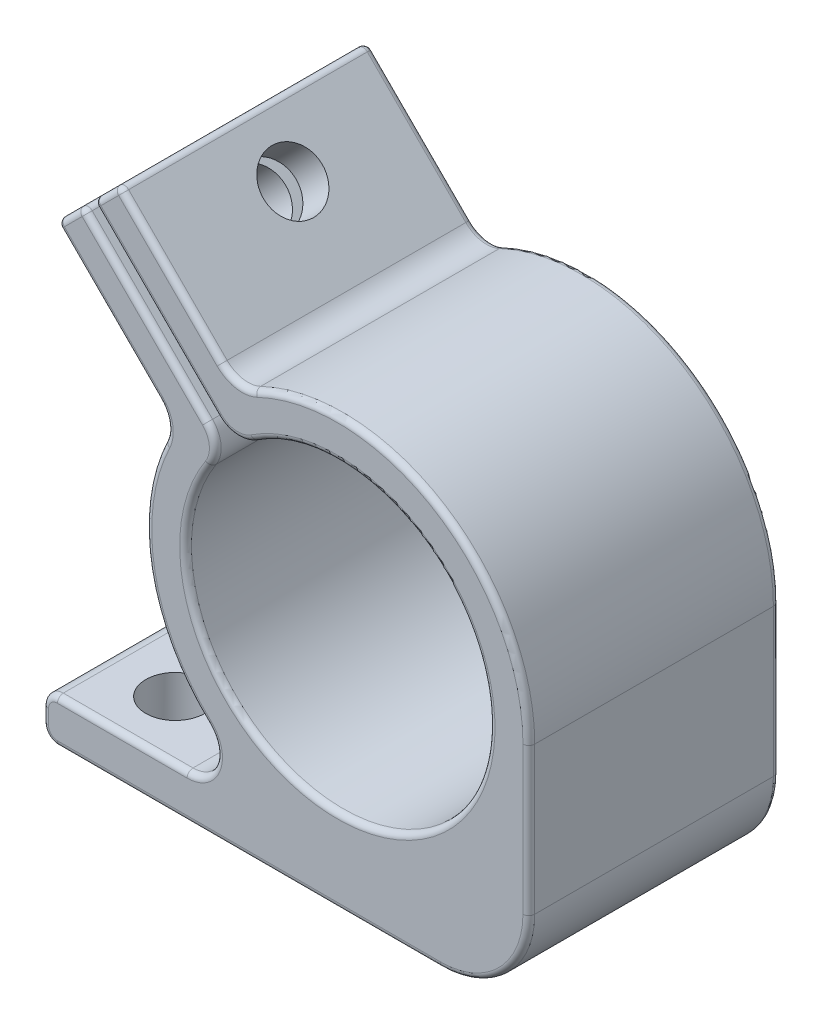
SolidWorks part; units mm, degrees
ref_plane "前视基准面" through (0, 0, 0) normal (0, 0, 1) x (1, 0, 0)
ref_plane "上视基准面" through (0, 0, 0) normal (0, 1, 0) x (1, 0, 0)
ref_plane "右视基准面" through (0, 0, 0) normal (1, 0, 0) x (0, 0, -1)
sketch "草图1" plane through (0, 0, 0) normal (0, 0, 1) x (1, 0, 0)
  line L0 (-9.5, -6.5) -> (-5.099, -6.5)
  line L1 (-9.5, -8) -> (3.5, -8)
  line L2 (-10, -7) -> (-10, -7.5)
  line L5 (0, 0) -> (-8.4853, 8.4853) construction
  line L6 (-7.2832, 9.4045) -> (-3.9393, 6.0607)
  line L7 (-8.8035, 8.1671) -> (-9.4045, 7.566)
  line L8 (0, 0) -> (0, -2.1091) construction
  line L9 (-8.1671, 8.5206) -> (-4.0812, 4.4347)
  line L10 (-8.1671, 8.8035) -> (-7.566, 9.4045)
  line L11 (-9.4045, 7.2832) -> (-6.0607, 3.9393)
  line L12 (6.5, 0) -> (6.5, -5)
  line L13 (-8.5206, 8.1671) -> (-4.4347, 4.0812)
  line L14 (0, 0) -> (0, -15.0845) construction
  arc A0 (-4.3057, 2.8254) -> (-2.8254, 4.3057) centre (0, 0) ccw
  arc A1 (-5.8654, 2.8013) -> (-4.4192, -4.7667) centre (0, 0) ccw
  arc A2 (6.5, -5) -> (3.5, -8) centre (3.5, -5) cw
  arc A3 (-4.4192, -4.7667) -> (-5.099, -6.5) centre (-5.099, -5.5) cw
  arc A6 (-9.5, -8) -> (-10, -7.5) centre (-9.5, -7.5) cw
  arc A7 (-10, -7) -> (-9.5, -6.5) centre (-9.5, -7) cw
  arc A8 (6.5, 0) -> (-2.8013, 5.8654) centre (0, 0) ccw
  arc A9 (-8.1671, 8.8035) -> (-8.1671, 8.5206) centre (-8.0257, 8.6621) ccw
  arc A10 (-7.2832, 9.4045) -> (-7.566, 9.4045) centre (-7.4246, 9.2631) ccw
  arc A11 (-3.9393, 6.0607) -> (-2.8013, 5.8654) centre (-3.2322, 6.7678) ccw
  arc A12 (-4.0812, 4.4347) -> (-2.8254, 4.3057) centre (-3.3741, 5.1418) ccw
  arc A13 (-9.4045, 7.2832) -> (-9.4045, 7.566) centre (-9.2631, 7.4246) cw
  arc A14 (-8.8035, 8.1671) -> (-8.5206, 8.1671) centre (-8.6621, 8.0257) cw
  arc A15 (-6.0607, 3.9393) -> (-5.8654, 2.8013) centre (-6.7678, 3.2322) cw
  arc A16 (-4.4347, 4.0812) -> (-4.3057, 2.8254) centre (-5.1418, 3.3741) cw
  point P13 (2.5981, -6.5)
  point P15 (0, -6.5)
  point P19 (0, -8)
  point P36 (-0.3, 12)
  dimension "D1" = 6.5
  dimension "D3" = 3
  dimension "D4" = 1
  dimension "D9" = 0.2
  dimension "D10" = 1
  dimension "D5" = 1.5
  dimension "D8" = 0.2
  dimension "D2" = 1.5
  dimension "D6" = 0.25
  dimension "D7" = 12
extrude "凸台-拉伸1" add sketch "草图1" along normal blind 8.5
sketch "草图3" plane through (0, -6.5, 0) normal (0, 1, 0) x (1, 0, 0)
  line L0 (-5.099, 0) -> (-9.5, 0) construction
  line L1 (-5.099, -8.5) -> (-9.5, -8.5) construction
  circle A0 centre (-7.5, -2) radius 1
  circle A1 centre (-7.5, -6.5) radius 1
  point P8 (-7.2995, -8.5)
  dimension "D1" = 2
  dimension "D2" = 2
  dimension "D3" = 2
extrude "切除-拉伸1" cut sketch "草图3" against normal up to next
fillet "圆角2" radius 0.2 50 edges at (3.4671, 5.4981, 0) (-7.2995, -6.5, 0) (-9.8536, -6.6464, 0) (-10, -7.25, 0) (-9.8536, -7.8536, 0) (-3, -8, 0) (-3, -8, 8.5) (-9.8536, -7.8536, 8.5) (-10, -7.25, 8.5) (-9.8536, -6.6464, 8.5) (-7.2995, -6.5, 8.5) (3.4671, 5.4981, 8.5) (3.6416, -3.6416, 8.5) (3.6416, -3.6416, 0) (-6.3845, -1.2201, 8.5) (-5.7822, 3.4013, 8.5) (-7.7326, 5.6113, 8.5) (-9.4631, 7.4246, 8.5) (-9.104, 7.8666, 8.5) (-8.6621, 8.2257, 8.5) (-6.4777, 6.1241, 8.5) (-4.147, 3.4762, 8.5) (-3.4762, 4.147, 8.5) (-6.1241, 6.4777, 8.5) (-8.2257, 8.6621, 8.5) (-7.8666, 9.104, 8.5) (-7.4246, 9.4631, 8.5) (-5.6113, 7.7326, 8.5) (-3.4013, 5.7822, 8.5) (-3.4013, 5.7822, 0) (-5.6113, 7.7326, 0) (-7.4246, 9.4631, 0) (-7.8666, 9.104, 0) (-8.2257, 8.6621, 0) (-6.1241, 6.4777, 0) (-3.4762, 4.147, 0) (-4.147, 3.4762, 0) (-6.4777, 6.1241, 0) (-8.6621, 8.2257, 0) (-9.104, 7.8666, 0) (-9.4631, 7.4246, 0) (-7.7326, 5.6113, 0) (-5.7822, 3.4013, 0) (-6.3845, -1.2201, 0) (6.5, -2.5, 8.5) (5.6213, -7.1213, 8.5) (5.6213, -7.1213, 0) (6.5, -2.5, 0) (-4.1681, -5.8651, 8.5) (-4.1681, -5.8651, 0)
sketch "草图5" plane through (-1.0607, -1.0607, 0) normal (-0.7071, -0.7071, 0) x (0, 0, 1)
  line L0 (0, 7.0711) -> (0, 11.8) construction
  circle A0 centre (4, 10) radius 1
  dimension "D1" = 4
extrude "切除-拉伸3" cut sketch "草图5" against normal blind 10
